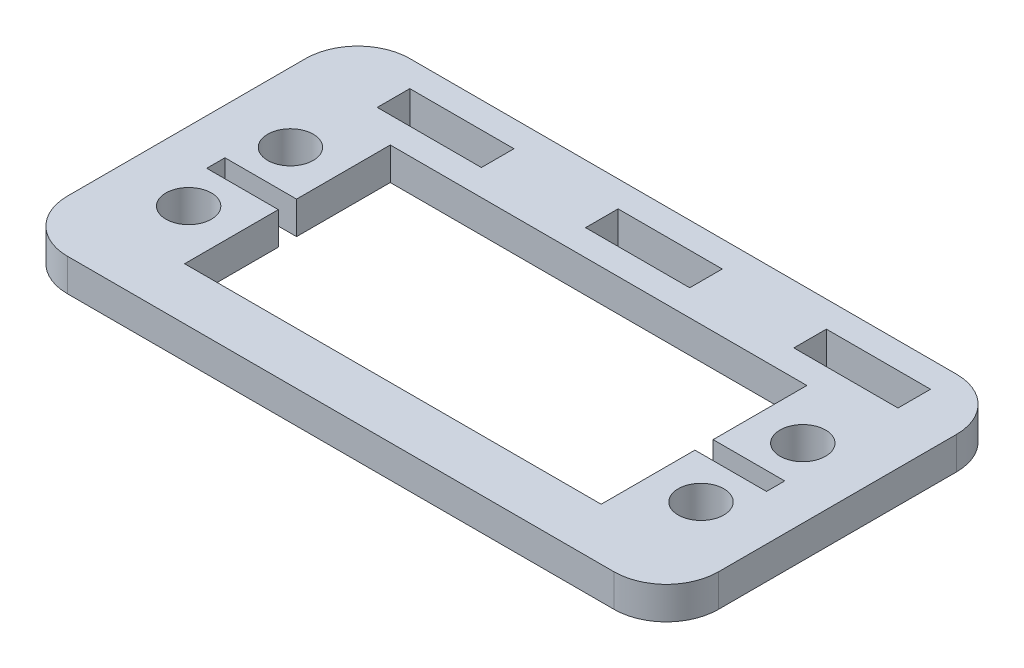
SolidWorks part; units mm, degrees
ref_plane "Front Plane" through (0, 0, 0) normal (0, 0, 1) x (1, 0, 0)
ref_plane "Top Plane" through (0, 0, 0) normal (0, 1, 0) x (1, 0, 0)
ref_plane "Right Plane" through (0, 0, 0) normal (1, 0, 0) x (0, 0, -1)
sketch "Sketch1" plane through (0, 0, 0) normal (0, 1, 0) x (1, 0, 0)
  line L0 (26.67, -10.033) -> (31.75, -10.033) construction
  line L1 (31.75, 18.288) -> (-31.75, 18.288)
  line L2 (31.75, 18.288) -> (31.75, -15.113)
  line L3 (31.75, -15.113) -> (-31.75, -15.113)
  line L4 (-31.75, 18.288) -> (-31.75, -15.113)
  line L5 (26.67, -10.033) -> (26.67, -15.113) construction
  line L6 (-26.67, -10.033) -> (-31.75, -10.033) construction
  line L7 (-26.67, 10.033) -> (26.67, 10.033) construction
  line L8 (-26.67, 10.033) -> (-26.67, -10.033) construction
  line L9 (-26.67, -10.033) -> (26.67, -10.033) construction
  line L10 (26.67, 10.033) -> (26.67, -10.033) construction
  line L11 (-26.67, 10.033) -> (26.67, -10.033) construction
  line L12 (-26.67, -10.033) -> (26.67, 10.033) construction
  line L13 (26.67, 15.748) -> (26.67, 18.288) construction
  line L14 (26.67, 15.748) -> (16.51, 15.748)
  line L15 (26.67, 15.748) -> (26.67, 12.573)
  line L16 (26.67, 12.573) -> (16.51, 12.573)
  line L17 (16.51, 15.748) -> (16.51, 12.573)
  line L18 (26.67, 15.748) -> (16.51, 12.573) construction
  line L19 (26.67, 12.573) -> (16.51, 15.748) construction
  line L20 (26.67, 12.573) -> (26.67, 10.033) construction
  line L21 (6.35, 15.748) -> (6.35, 12.573)
  line L22 (6.35, 15.748) -> (-3.81, 15.748)
  line L23 (6.35, 12.573) -> (-3.81, 12.573)
  line L24 (-3.81, 15.748) -> (-3.81, 12.573)
  line L25 (-13.97, 15.748) -> (-13.97, 12.573)
  line L26 (-13.97, 15.748) -> (-24.13, 15.748)
  line L27 (-13.97, 12.573) -> (-24.13, 12.573)
  line L28 (-24.13, 15.748) -> (-24.13, 12.573)
  line L30 (-20.32, -10.033) -> (20.32, -10.033)
  line L31 (-20.32, -10.033) -> (-20.32, 10.033)
  line L32 (-20.32, 10.033) -> (20.32, 10.033)
  line L33 (20.32, -10.033) -> (20.32, 10.033)
  line L34 (-20.32, -10.033) -> (20.32, 10.033) construction
  line L35 (-20.32, 10.033) -> (20.32, -10.033) construction
  point P0 (0, 0)
  point P4 (21.59, 14.1605)
  point P6 (0, 0)
  point P20 (0, 0)
  dimension "D1" = 20.066
  dimension "D2" = 53.34
  dimension "D3" = 5.08
  dimension "D4" = 3.175
  dimension "D5" = 10.16
  dimension "D6" = 2.54
  dimension "D7" = 3
  dimension "D8" = 6.35
extrude "Main Extrusion" add sketch "Sketch1" along normal blind 3.175
sketch "Sketch3" plane through (0, 3.175, 0) normal (0, 1, 0) x (1, 0, 0)
  line L0 (-26.7208, 6.3627) -> (-26.7208, 3.5687) construction
  line L1 (26.7208, -9.9949) -> (-26.7208, -9.9949) construction
  line L2 (26.7208, -9.9949) -> (26.7208, 9.9949) construction
  line L3 (26.7208, 9.9949) -> (-26.7208, 9.9949) construction
  line L5 (26.7208, -9.9949) -> (-26.7208, 9.9949) construction
  line L6 (26.7208, 9.9949) -> (-26.7208, -9.9949) construction
  line L7 (-26.7208, -3.5687) -> (-26.7208, -6.3627) construction
  line L8 (-26.7208, -6.3627) -> (-26.7208, -9.9949) construction
  line L9 (-26.7208, 6.3627) -> (-26.7208, 9.9949) construction
  line L10 (-24.9922, 4.9657) -> (-24.9922, -4.9657) construction
  line L14 (0, 9.9949) -> (0, -9.9949) construction
  circle A0 centre (-24.9922, 4.9657) radius 2.2225
  circle A1 centre (-24.9922, -4.9657) radius 2.2225
  circle A2 centre (24.9922, -4.9657) radius 2.2225
  circle A3 centre (24.9922, 4.9657) radius 2.2225
  point P0 (0, 0)
  point P12 (0, 0)
  point P16 (-23.989, 3.953)
  point P22 (-26.7208, -5.0533)
  point P23 (-26.7208, 3.6812)
  point P24 (-26.7208, -5.7756)
  point P25 (0, 0)
  dimension "D3" = 4.445
  dimension "D1" = 53.4416
  dimension "D2" = 19.9898
  dimension "D4" = 2.794
  dimension "D5" = 9.9314
extrude "Mounting Holes" cut sketch "Sketch3" against normal through all
sketch "Sketch5" plane through (0, 3.175, 0) normal (0, 1, 0) x (1, 0, 0)
  line L0 (-20.32, 0) -> (-20.32, 0.889)
  line L1 (-20.32, 10.033) -> (-20.32, -10.033) construction
  line L2 (-20.32, 0.889) -> (-27.305, 0.889)
  line L3 (-27.305, 0.889) -> (-27.305, -0.889)
  line L4 (-27.305, -0.889) -> (-20.32, -0.889)
  line L5 (-20.32, -0.889) -> (-20.32, 0)
  line L6 (0, 10.033) -> (0, -10.033) construction
  line L7 (20.32, 10.033) -> (-20.32, 10.033) construction
  line L8 (-20.32, -10.033) -> (20.32, -10.033) construction
  line L9 (27.305, -0.889) -> (20.32, -0.889)
  line L10 (27.305, 0.889) -> (27.305, -0.889)
  line L11 (20.32, 0.889) -> (27.305, 0.889)
  line L12 (20.32, -0.889) -> (20.32, 0)
  line L13 (20.32, 0) -> (20.32, 0.889)
  dimension "D1" = 6.985
  dimension "D2" = 1.778
extrude "Tab cutout" cut sketch "Sketch5" against normal through all
fillet "Fillet1" radius 5.08 4 edges at (31.75, 1.5875, -18.288) (31.75, 1.5875, 15.113) (-31.75, 1.5875, 15.113) (-31.75, 1.5875, -18.288)
sketch "Kerf Adjusted Sketch" plane through (0, 3.175, 0) normal (0, 1, 0) x (1, 0, 0)
  line L20 (-24.0538, 15.6718) -> (-24.0538, 12.6492)
  line L21 (-14.0462, 15.6718) -> (-24.0538, 15.6718)
  line L22 (-14.0462, 12.6492) -> (-14.0462, 15.6718)
  line L23 (-24.0538, 12.6492) -> (-14.0462, 12.6492)
  line L24 (-24.0538, 15.6718) -> (-24.0538, 12.6492)
  line L25 (-14.0462, 15.6718) -> (-24.0538, 15.6718)
  line L26 (-14.0462, 12.6492) -> (-14.0462, 15.6718)
  line L27 (-24.0538, 12.6492) -> (-14.0462, 12.6492)
  line L32 (-3.7338, 15.6718) -> (-3.7338, 12.6492)
  line L33 (6.2738, 15.6718) -> (-3.7338, 15.6718)
  line L34 (6.2738, 12.6492) -> (6.2738, 15.6718)
  line L35 (-3.7338, 12.6492) -> (6.2738, 12.6492)
  line L36 (-3.7338, 15.6718) -> (-3.7338, 12.6492)
  line L37 (6.2738, 15.6718) -> (-3.7338, 15.6718)
  line L38 (6.2738, 12.6492) -> (6.2738, 15.6718)
  line L39 (-3.7338, 12.6492) -> (6.2738, 12.6492)
  line L44 (26.5938, 12.6492) -> (26.5938, 15.6718)
  line L45 (26.5938, 15.6718) -> (16.5862, 15.6718)
  line L46 (16.5862, 15.6718) -> (16.5862, 12.6492)
  line L47 (16.5862, 12.6492) -> (26.5938, 12.6492)
  line L48 (26.5938, 12.6492) -> (26.5938, 15.6718)
  line L49 (26.5938, 15.6718) -> (16.5862, 15.6718)
  line L50 (16.5862, 15.6718) -> (16.5862, 12.6492)
  line L51 (16.5862, 12.6492) -> (26.5938, 12.6492)
  line L126 (31.8262, -10.033) -> (31.8262, 13.208)
  line L127 (-26.67, -15.1892) -> (26.67, -15.1892)
  line L128 (-31.8262, 13.208) -> (-31.8262, -10.033)
  line L129 (26.67, 18.3642) -> (-26.67, 18.3642)
  line L130 (27.2288, -0.8128) -> (27.2288, 0.8128)
  line L131 (20.2438, 0.8128) -> (20.2438, 9.9568)
  line L132 (27.2288, 0.8128) -> (20.2438, 0.8128)
  line L133 (20.2438, -0.8128) -> (27.2288, -0.8128)
  line L134 (20.2438, -9.9568) -> (20.2438, -0.8128)
  line L135 (-20.2438, -9.9568) -> (20.2438, -9.9568)
  line L136 (-20.2438, -0.8128) -> (-20.2438, -9.9568)
  line L137 (-27.2288, 0.8128) -> (-27.2288, -0.8128)
  line L138 (-27.2288, -0.8128) -> (-20.2438, -0.8128)
  line L139 (-20.2438, 0.8128) -> (-27.2288, 0.8128)
  line L140 (-20.2438, 9.9568) -> (-20.2438, 0.8128)
  line L141 (20.2438, 9.9568) -> (-20.2438, 9.9568)
  line L142 (27.2288, -0.8128) -> (27.2288, 0.8128)
  line L143 (20.2438, 0.8128) -> (20.2438, 9.9568)
  line L144 (27.2288, 0.8128) -> (20.2438, 0.8128)
  line L145 (20.2438, -0.8128) -> (27.2288, -0.8128)
  line L146 (20.2438, -9.9568) -> (20.2438, -0.8128)
  line L147 (-20.2438, -9.9568) -> (20.2438, -9.9568)
  line L148 (-20.2438, -0.8128) -> (-20.2438, -9.9568)
  line L149 (-27.2288, 0.8128) -> (-27.2288, -0.8128)
  line L150 (-27.2288, -0.8128) -> (-20.2438, -0.8128)
  line L151 (-20.2438, 0.8128) -> (-27.2288, 0.8128)
  line L152 (-20.2438, 9.9568) -> (-20.2438, 0.8128)
  line L153 (20.2438, 9.9568) -> (-20.2438, 9.9568)
  line L154 (31.8262, -10.033) -> (31.8262, 13.208)
  line L155 (-26.67, -15.1892) -> (26.67, -15.1892)
  line L156 (-31.8262, 13.208) -> (-31.8262, -10.033)
  line L157 (26.67, 18.3642) -> (-26.67, 18.3642)
  circle A18 centre (-24.9922, 4.9657) radius 2.1463
  circle A19 centre (-24.9922, 4.9657) radius 2.1463
  circle A21 centre (-24.9922, -4.9657) radius 2.1463
  circle A22 centre (-24.9922, -4.9657) radius 2.1463
  circle A24 centre (24.9922, -4.9657) radius 2.1463
  circle A25 centre (24.9922, -4.9657) radius 2.1463
  circle A27 centre (24.9922, 4.9657) radius 2.1463
  circle A28 centre (24.9922, 4.9657) radius 2.1463
  arc A37 (26.67, -15.1892) -> (31.8262, -10.033) centre (26.67, -10.033) ccw
  arc A38 (-31.8262, -10.033) -> (-26.67, -15.1892) centre (-26.67, -10.033) ccw
  arc A39 (-26.67, 18.3642) -> (-31.8262, 13.208) centre (-26.67, 13.208) ccw
  arc A40 (31.8262, 13.208) -> (26.67, 18.3642) centre (26.67, 13.208) ccw
  arc A41 (26.67, -15.1892) -> (31.8262, -10.033) centre (26.67, -10.033) ccw
  arc A42 (-31.8262, -10.033) -> (-26.67, -15.1892) centre (-26.67, -10.033) ccw
  arc A43 (-26.67, 18.3642) -> (-31.8262, 13.208) centre (-26.67, 13.208) ccw
  arc A44 (31.8262, 13.208) -> (26.67, 18.3642) centre (26.67, 13.208) ccw
  dimension "D1" = 0.0762
  dimension "D2" = 0.0762
  dimension "D3" = 0.0762
  dimension "D4" = 0.0762
  dimension "D5" = 0.0762
  dimension "D6" = 0.0762
  dimension "D7" = 0.0762
  dimension "D8" = 0.0762
  dimension "D9" = 0.0762
